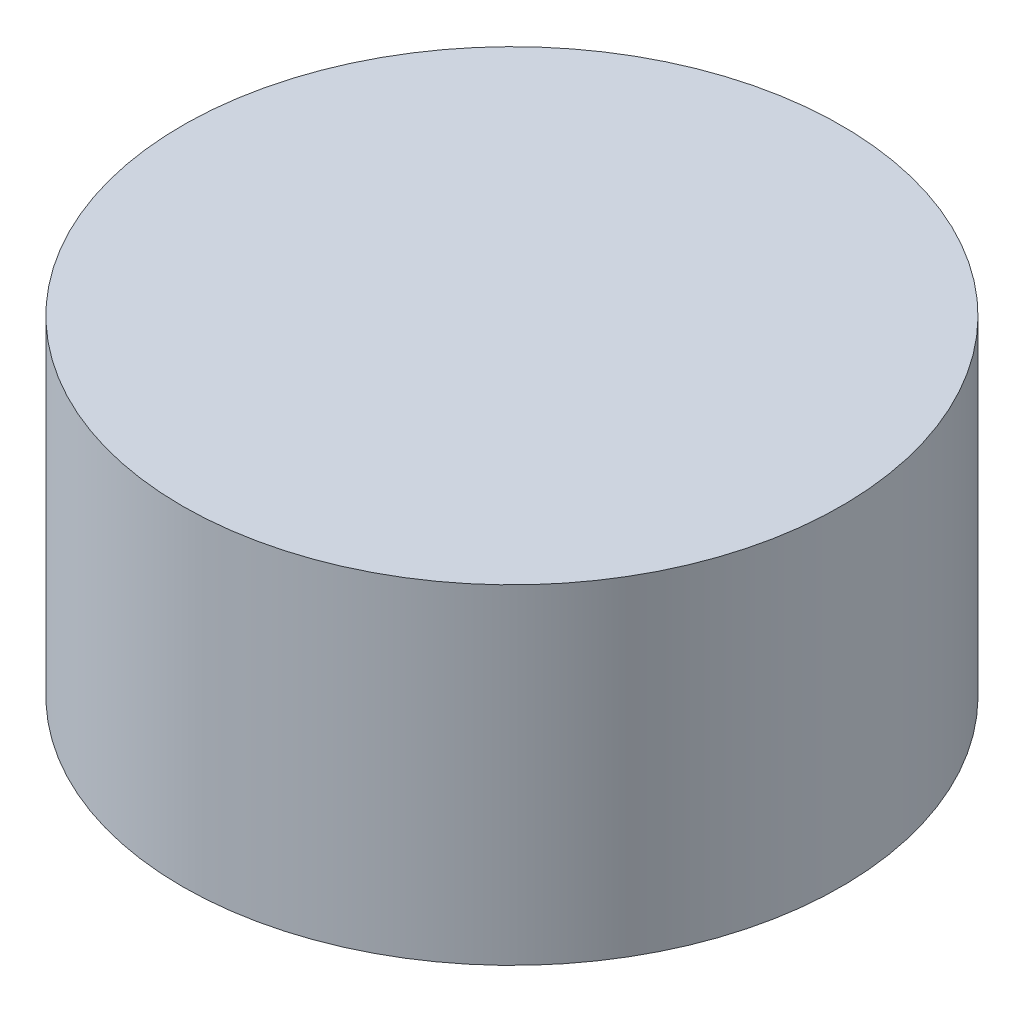
SolidWorks part; units mm, degrees
material "Titanium"
ref_plane "Front Plane" through (0, 0, 0) normal (0, 0, 1) x (1, 0, 0)
ref_plane "Top Plane" through (0, 0, 0) normal (0, 1, 0) x (1, 0, 0)
ref_plane "Right Plane" through (0, 0, 0) normal (1, 0, 0) x (0, 0, -1)
sketch "Sketch1" plane through (0, 0, 0) normal (0, 1, 0) x (1, 0, 0)
  circle A0 centre (0, 0) radius 5
  dimension "D1" = 10
extrude "Boss-Extrude1" add sketch "Sketch1" along normal blind 5
